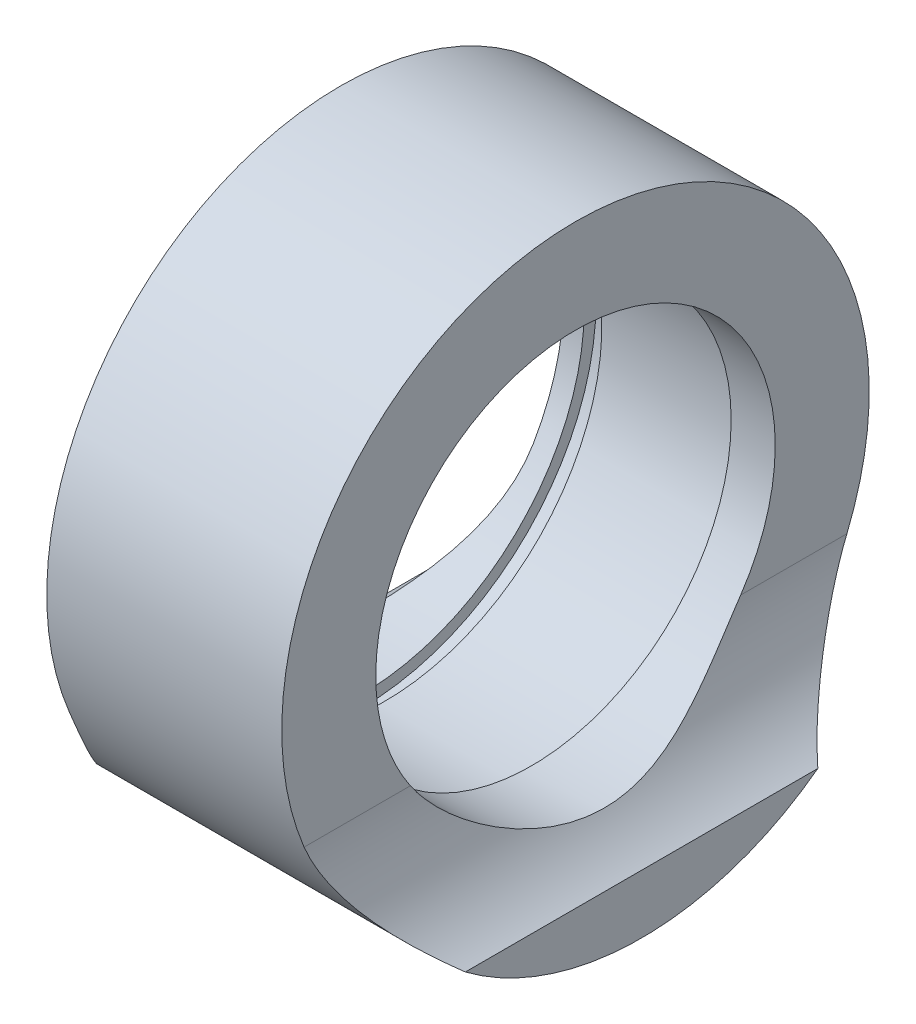
SolidWorks part; units mm, degrees
ref_plane "Front Plane" through (0, 0, 0) normal (0, 0, 1) x (1, 0, 0)
ref_plane "Top Plane" through (0, 0, 0) normal (0, 1, 0) x (1, 0, 0)
ref_plane "Right Plane" through (0, 0, 0) normal (1, 0, 0) x (0, 0, -1)
sketch "Sketch2" plane through (0, 0, 0) normal (0, 1, 0) x (1, 0, 0)
  line L0 (7.9375, 0) -> (7.9375, 12.7) construction
  line L1 (0, 0) -> (15.875, 0) construction
  line L2 (0, 0) -> (0, 12.7) construction
  line L3 (0, 12.7) -> (15.875, 12.7) construction
  line L4 (15.875, 0) -> (15.875, 12.7) construction
  line L5 (0, 9.398) -> (15.875, 9.398) construction
  line L6 (0, 10.16) -> (15.875, 10.16) construction
  line L7 (0, 8.636) -> (15.875, 8.636) construction
  line L8 (4.7625, 12.7) -> (4.7625, 0) construction
  line L9 (11.1125, 12.7) -> (11.1125, 0) construction
  line L10 (4.7625, 9.398) -> (11.1125, 9.398)
  line L11 (3.7465, 12.7) -> (3.7465, 0) construction
  line L12 (4.7625, 9.398) -> (4.7625, 10.16)
  line L13 (3.7465, 10.16) -> (3.7465, 9.652)
  line L14 (3.7465, 10.16) -> (4.7625, 10.16)
  line L15 (3.7465, 9.652) -> (0, 9.652)
  line L16 (11.1125, 9.398) -> (11.1125, 8.636)
  line L17 (11.1125, 8.636) -> (15.875, 8.636)
  line L18 (15.875, 8.636) -> (15.875, 12.7)
  line L19 (15.875, 12.7) -> (0, 12.7)
  line L20 (0, 12.7) -> (0, 9.652)
  dimension "D1" = 15.875
  dimension "D2" = 12.7
  dimension "D3" = 9.398
  dimension "D4" = 10.16
  dimension "D5" = 8.636
  dimension "D6" = 3.175
  dimension "D7" = 3.175
  dimension "D8" = 1.016
  dimension "D9" = 0.254
revolve "Revolve1" add sketch "Sketch2" angle 360 about L1
sketch "Sketch6" plane through (0, 0, 0) normal (0, 0, 1) x (1, 0, 0)
  line L0 (7.9375, 12.7) -> (7.9375, -12.7) construction
  line L1 (15.875, 12.7) -> (0, 12.7) construction
  line L2 (0, -12.7) -> (15.875, -12.7) construction
  line L3 (0, -10.16) -> (15.875, -10.16) construction
  line L4 (0, 12.7) -> (0, -12.7) construction
  line L5 (15.875, -12.7) -> (15.875, 12.7) construction
  line L6 (2.8575, -4.8567) -> (2.8575, 12.7)
  line L7 (2.8575, 12.7) -> (13.0175, 12.7) construction
  line L8 (13.0175, 12.7) -> (13.0175, -4.8567)
  line L9 (15.875, -10.16) -> (15.875, 12.7)
  line L10 (15.875, 12.7) -> (13.0175, 12.7)
  line L11 (2.8575, 12.7) -> (0, 12.7)
  line L12 (0, 12.7) -> (0, -10.16)
  arc A0 (0, -10.16) -> (2.8575, -4.8567) centre (-3.4925, -4.8567) ccw
  arc A1 (15.875, -10.16) -> (13.0175, -4.8567) centre (19.3675, -4.8567) cw
  dimension "D4" = 6.35
  dimension "D1" = 2.54
  dimension "D2" = 5.08
  dimension "D3" = 5.08
extrude "Cut-Extrude1" cut sketch "Sketch6" against normal through all and the other way through all contours L12 A0 L6 L11 | A1 L9 L10 L8
sketch "Sketch7" plane through (0, 0, 0) normal (1, 0, 0) x (0, 0, -1)
  line L0 (0, 0) -> (0, -21.8409) construction
  line L1 (0, 0) -> (-9.7585, -25.4217) construction
  line L2 (0, 0) -> (8.8027, -22.9318) construction
  point P6 (0, 0)
  dimension "D1" = 21
  dimension "D2" = 21
ref_plane "Plane1" through (0, 0, 0) normal (0, -0.9336, 0.3584) x (-1, 0, 0)
ref_plane "Plane2" through (0, 0, 0) normal (0, -0.9336, -0.3584) x (-1, 0, 0)
sketch "Sketch8" plane through (0, 0, 0) normal (0, -0.9336, 0.3584) x (-1, 0, 0)
  line L0 (0, 0) -> (-15.875, 0) construction
  line L1 (-15.875, 10.7549) -> (-15.875, -3.4729) construction
  circle A0 centre (-7.9375, 0) radius 7.9375
  dimension "D1" = 15.875
